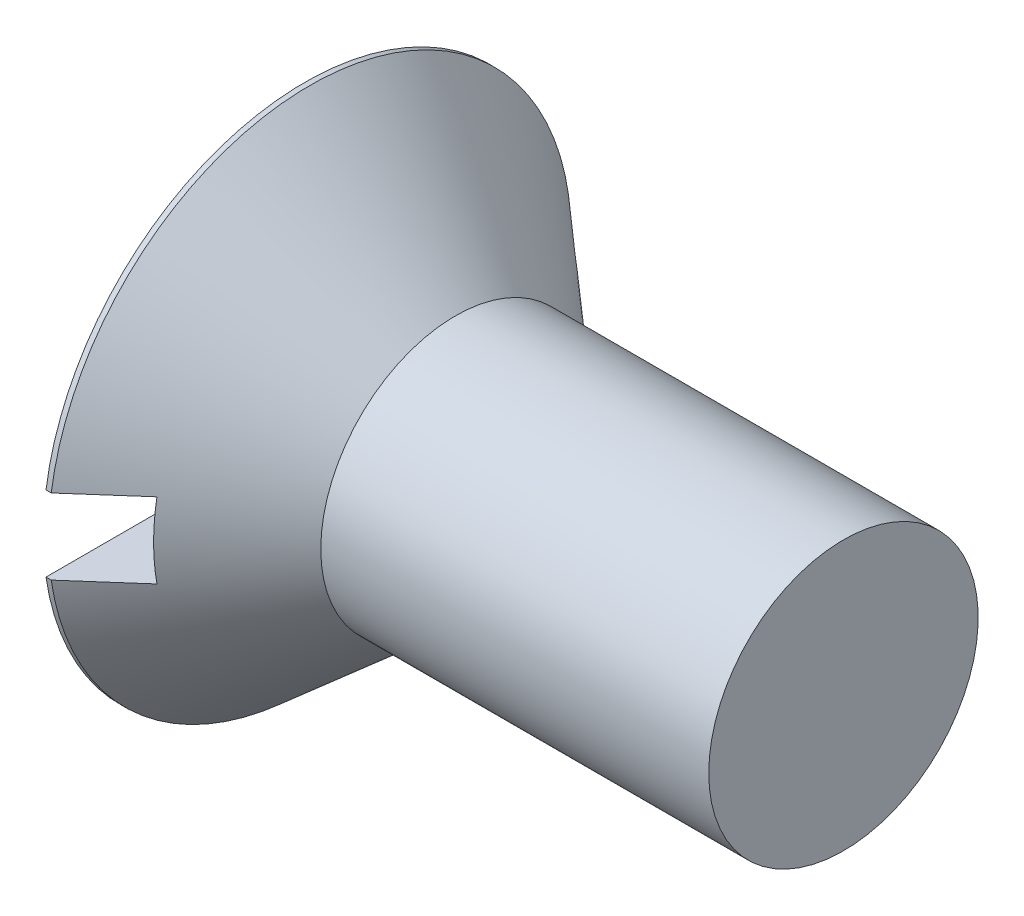
SolidWorks part; units mm, degrees
revolve "Base-Revolve" add sketch "BodySke" angle 360 about L5
sketch "BodySke" plane through (0, 0, 0) normal (0, 0, 1) x (1, 0, 0)
  line L0 (0, 0) -> (0, 6.1595)
  line L1 (0, 6.1595) -> (0.1227, 6.1595)
  line L2 (3.556, 3.175) -> (12.7, 3.175)
  line L3 (12.7, 3.175) -> (12.7, 0)
  line L4 (12.7, 0) -> (0, 0)
  line L5 (-6.35, 0) -> (82.55, 0) construction
  line L6 (3.556, -3.175) -> (12.7, -3.175) construction
  line L7 (0.1227, -6.1595) -> (3.556, -3.175) construction
  line L8 (0.1227, 6.1595) -> (3.556, 3.175)
  line L9 (0, -6.1595) -> (0.1227, -6.1595) construction
  line L10 (4.826, 4.7625) -> (4.826, -4.7625) construction
  line L11 (0, 6.35) -> (0, -3.175) construction
  dimension "Diameter" = 6.35
  dimension "Length" = 12.7
  dimension "Head_ht" = 3.556
  dimension "Head_dia" = 12.319
  dimension "Head_ang" = 82
  dimension "D6" = 0.1227
  dimension "Advance" = 1.27
  dimension "Thread_nom" = 12.7
cosmetic thread "ThreadCosmetic" [suppressed] parameters "Thread_length"=7.874, "Thread_minor"=4.8387
extrude "Slot" cut sketch "Sketch6" against normal blind 1.4478
sketch "Sketch6" plane through (0, 0, 0) normal (-1, 0, 0) x (0, 0, 1)
  line L0 (-6.1595, -0.889) -> (6.1595, -0.889)
  line L1 (-6.1595, -0.889) -> (-6.1595, 0.889)
  line L2 (6.1595, 0.889) -> (-6.1595, 0.889)
  line L3 (6.1595, 0.889) -> (6.1595, -0.889)
  dimension "Slot_width" = 1.778
  dimension "D1" = 0.889
  dimension "D2" = 12.319
  dimension "D3" = 6.1595
ref_plane "Plane1" through (0, 0, 0) normal (0, 0, 1) x (1, 0, 0)
ref_plane "Plane2" through (0, 0, 0) normal (0, 1, 0) x (1, 0, 0)
ref_plane "Plane3" through (0, 0, 0) normal (1, 0, 0) x (0, 0, -1)
sketch "ThdSchSke" plane through (0, 0, 0) normal (0, 0, 1) x (1, 0, 0)
  line L0 (4.826, -2.4194) -> (4.2969, -3.175)
  line L1 (4.826, -2.4194) -> (5.3551, -3.175)
  line L2 (5.3551, -3.175) -> (5.3551, -3.9688)
  line L3 (-3.175, 0) -> (5.1513, 0) construction
  line L5 (5.3551, -3.9688) -> (4.2969, -3.9688)
  line L6 (4.2969, -3.9688) -> (4.2969, -3.175)
  line L7 (0, 6.1595) -> (0, 0.889) construction
  dimension "Diameter" = 6.35
  dimension "Thread_minor" = 4.8387
  dimension "Start" = 4.826
revolve "ThreadSchematic" [suppressed] cut sketch "ThdSchSke" angle 360 about L3
pattern_linear "ThdSchPat" [suppressed]
equation "\"D1@Sketch6\" = \"Slot_width@Sketch6\" / 2"
equation "\"D2@Sketch6\" = \"Head_dia@BodySke\""
equation "\"D3@Sketch6\" = \"D2@Sketch6\" / 2"
equation "\"Thread_length@ThreadCosmetic\" = ((sgn( (\"Length@BodySke\" - \"Advance@BodySke\" - \"Head_ht@BodySke\" ) - \"Thread_nom@BodySke\" )-1)*( (\"Length@BodySke\" - \"Advance@BodySke\" - \"Head_ht@BodySke\" ) - \"Thread_nom@BodySke\" ))/-2+ \"Thread_nom@BodySke\""
equation "\"Thread_minor@ThdSchSke\" = \"Thread_minor@ThreadCosmetic\""
equation "\"Diameter@ThdSchSke\" = \"Diameter@BodySke\""
equation "\"Overcut@ThdSchSke\" = \"Diameter@BodySke\" * 1.25"
equation "\"Start@ThdSchSke\" = 0.000001 + \"Length@BodySke\" - \"Thread_length@ThreadCosmetic\"  '---Countersunk---"
equation "\"Num_threads@ThdSchPat\" = int( \"Thread_length@ThreadCosmetic\" / \"Advance@BodySke\" + 0.999 )  + 1"
equation "\"Advance@ThdSchPat\" = \"Thread_length@ThreadCosmetic\" /  (\"Num_threads@ThdSchPat\" - 1) 'relax it"
